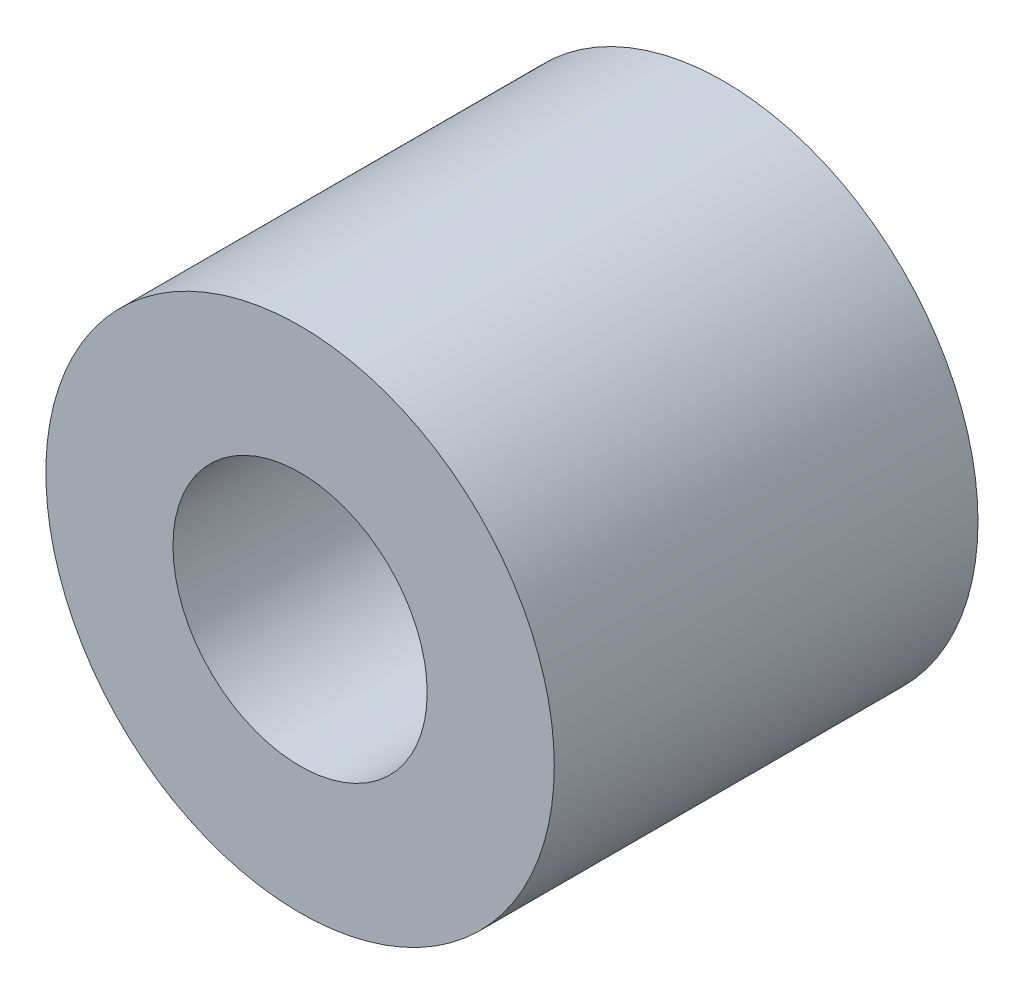
SolidWorks part; units mm, degrees
ref_plane "前视基准面" through (0, 0, 0) normal (0, 0, 1) x (1, 0, 0)
ref_plane "上视基准面" through (0, 0, 0) normal (0, 1, 0) x (1, 0, 0)
ref_plane "右视基准面" through (0, 0, 0) normal (1, 0, 0) x (0, 0, -1)
sketch "草图1" plane through (0, 0, 0) normal (0, 0, 1) x (1, 0, 0)
  circle A0 centre (0, 0) radius 6
  circle A1 centre (0, 0) radius 3
  dimension "D1" = 12
  dimension "D2" = 6
extrude "凸台-拉伸1" add sketch "草图1" along normal mid plane 10
